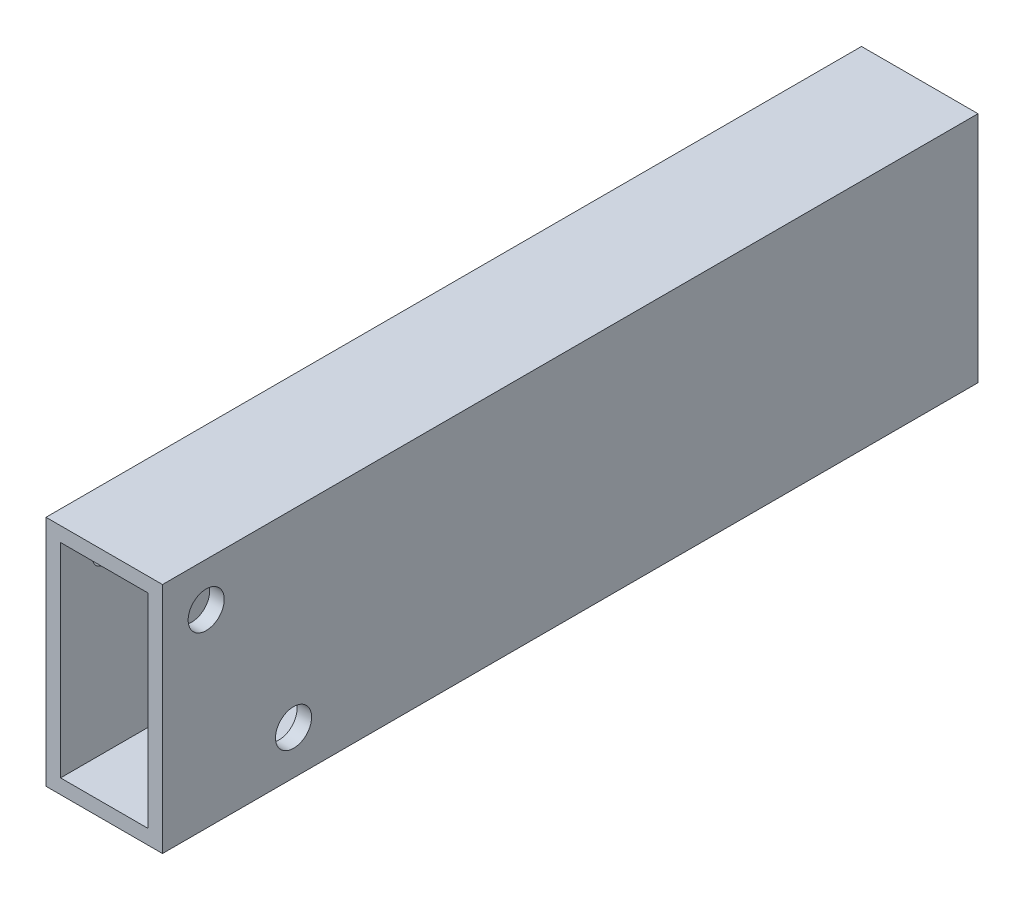
SolidWorks part; units mm, degrees
ref_plane "Front Plane" through (0, 0, 0) normal (0, 0, 1) x (1, 0, 0)
ref_plane "Top Plane" through (0, 0, 0) normal (0, 1, 0) x (1, 0, 0)
ref_plane "Right Plane" through (0, 0, 0) normal (1, 0, 0) x (0, 0, -1)
sketch "Sketch1" plane through (0, 0, 0) normal (0, 0, 1) x (1, 0, 0)
  line L0 (-9.525, 22.225) -> (9.525, 22.225)
  line L1 (-12.7, -25.4) -> (12.7, -25.4)
  line L2 (-12.7, -25.4) -> (-12.7, 25.4)
  line L3 (-12.7, 25.4) -> (12.7, 25.4)
  line L4 (12.7, -25.4) -> (12.7, 25.4)
  line L5 (-12.7, -25.4) -> (12.7, 25.4) construction
  line L6 (-12.7, 25.4) -> (12.7, -25.4) construction
  line L7 (9.525, -22.225) -> (9.525, 22.225)
  line L8 (-9.525, -22.225) -> (9.525, -22.225)
  line L9 (-9.525, -22.225) -> (-9.525, 22.225)
  point P0 (0, 0)
  dimension "D1" = 50.8
  dimension "D2" = 25.4
  dimension "D3" = 3.175
extrude "Boss-Extrude1" add sketch "Sketch1" along normal blind 177.8
sketch "Sketch2" plane through (12.7, 0, 0) normal (1, 0, 0) x (0, 0, -1)
  line L0 (-168.275, 15.875) -> (-177.8, 15.875) construction
  line L1 (-177.8, -25.4) -> (-177.8, 25.4) construction
  line L2 (-168.275, 15.875) -> (-168.275, 25.4) construction
  line L3 (-177.8, 25.4) -> (0, 25.4) construction
  line L4 (-168.275, -25.4) -> (-168.275, -15.875) construction
  line L5 (-177.8, -25.4) -> (0, -25.4) construction
  line L6 (-168.275, -15.875) -> (-149.225, -15.875) construction
  circle A0 centre (-168.275, 15.875) radius 2.5797
  circle A1 centre (-149.225, -15.875) radius 2.5797
  dimension "D1" = 5.1594
  dimension "D2" = 9.525
  dimension "D3" = 19.05
extrude "Cut-Extrude1" cut sketch "Sketch2" against normal through all
sketch "Sketch3" plane through (12.7, 0, 0) normal (1, 0, 0) x (0, 0, -1)
  circle A0 centre (-168.275, 15.875) radius 3.937
  circle A1 centre (-149.225, -15.875) radius 3.937
  dimension "D1" = 7.874
extrude "Cut-Extrude2" cut sketch "Sketch3" against normal up to next
